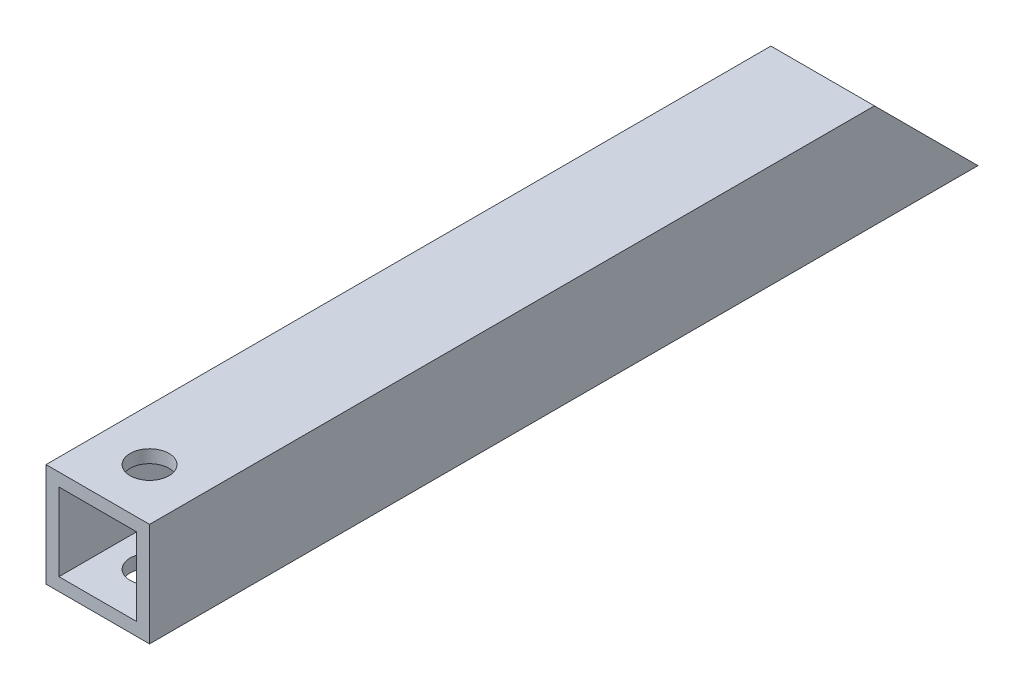
SolidWorks part; units mm, degrees
ref_plane "Front Plane" through (0, 0, 0) normal (0, 0, 1) x (1, 0, 0)
ref_plane "Top Plane" through (0, 0, 0) normal (0, 1, 0) x (1, 0, 0)
ref_plane "Right Plane" through (0, 0, 0) normal (1, 0, 0) x (0, 0, -1)
sketch "Sketch1" plane through (0, 0, 0) normal (0, 0, 1) x (1, 0, 0)
  line L0 (9.525, 9.525) -> (-9.525, 9.525)
  line L1 (12.7, -12.7) -> (-12.7, -12.7)
  line L2 (12.7, -12.7) -> (12.7, 12.7)
  line L3 (12.7, 12.7) -> (-12.7, 12.7)
  line L4 (-12.7, -12.7) -> (-12.7, 12.7)
  line L5 (12.7, -12.7) -> (-12.7, 12.7) construction
  line L6 (12.7, 12.7) -> (-12.7, -12.7) construction
  line L7 (-9.525, -9.525) -> (-9.525, 9.525)
  line L8 (9.525, -9.525) -> (-9.525, -9.525)
  line L9 (9.525, -9.525) -> (9.525, 9.525)
  point P0 (0, 0)
  dimension "D1" = 25.4
  dimension "D2" = 25.4
  dimension "D3" = 3.175
extrude "Boss-Extrude1" add sketch "Sketch1" along normal blind 203.2
sketch "Sketch2" plane through (12.7, 0, 0) normal (1, 0, 0) x (0, 0, -1)
  line L0 (0, 12.7) -> (0, -12.7)
  line L1 (0, -12.7) -> (-25.4, 12.7)
  line L2 (-203.2, 12.7) -> (0, 12.7) construction
  line L3 (-25.4, 12.7) -> (0, 12.7)
  line L4 (-203.2, -12.7) -> (0, -12.7) construction
  dimension "D1" = 45
extrude "Cut-Extrude1" cut sketch "Sketch2" against normal through all
sketch "Sketch3" plane through (0, -12.7, 0) normal (0, -1, 0) x (1, 0, 0)
  line L0 (-12.7, 203.2) -> (12.7, 203.2) construction
  point P0 (0, 190.5)
  dimension "D1" = 12.7
sketch "Sketch4" plane through (0, -12.7, 0) normal (0, -1, 0) x (-1, 0, 0)
  point P0 (0, -190.5)
hole_wizard "3/8 (0.375) Diameter Hole1" positions "Sketch4" profile "Sketch5" hole size "3/8" standard "ANSI Inch" end condition through all
sketch "Sketch5" plane through (0, -12.7, 190.5) normal (1, 0, 0) x (0, 0, -1)
  line L0 (0, 0) -> (0, 25.4)
  line L1 (0, 25.4) -> (4.7625, 25.4)
  line L2 (4.7625, 25.4) -> (4.7625, 0)
  line L5 (4.7625, 0) -> (0, 0)
  line L11 (0, -6.35) -> (0, 107.95) construction
  dimension "Thru Hole Dia." = 9.525
  dimension "Thru Hole Depth" = 25.4
